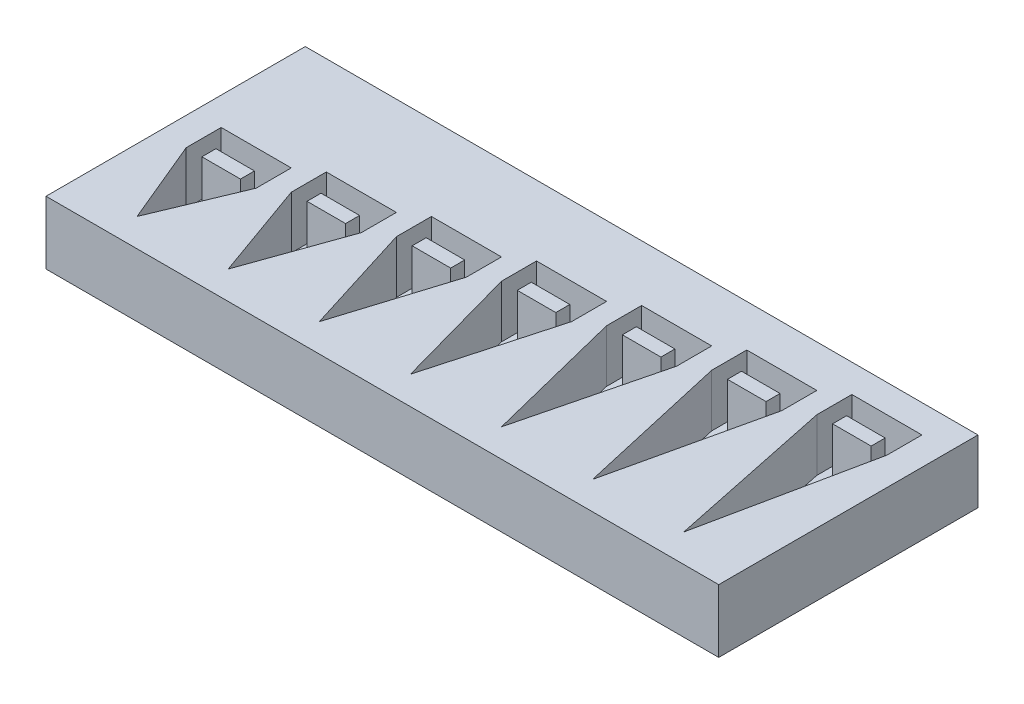
SolidWorks part; units mm, degrees
ref_plane "Front Plane" through (0, 0, 0) normal (0, 0, 1) x (1, 0, 0)
ref_plane "Top Plane" through (0, 0, 0) normal (0, 1, 0) x (1, 0, 0)
ref_plane "Right Plane" through (0, 0, 0) normal (1, 0, 0) x (0, 0, -1)
sketch "Flaps" plane through (0, 0, 0) normal (0, 1, 0) x (1, 0, 0)
  line L0 (0, 0) -> (0, 17) construction
  line L1 (0, 0) -> (-5, 12)
  line L2 (-5, 12) -> (-5, 17)
  line L3 (-5, 17) -> (5, 17)
  line L4 (5, 12) -> (5, 17)
  line L5 (0, 0) -> (5, 12)
  line L6 (13, 0) -> (13, 19) construction
  line L7 (-2.75, 14) -> (2.75, 14)
  line L8 (-2.75, 14) -> (-2.75, 12)
  line L9 (-2.75, 12) -> (2.75, 12)
  line L10 (2.75, 14) -> (2.75, 12)
  line L11 (13, 0) -> (8, 14)
  line L12 (8, 14) -> (8, 19)
  line L13 (8, 19) -> (18, 19)
  line L14 (18, 14) -> (18, 19)
  line L15 (13, 0) -> (18, 14)
  line L16 (10.25, 16) -> (15.75, 16)
  line L17 (10.25, 16) -> (10.25, 14)
  line L18 (10.25, 14) -> (15.75, 14)
  line L19 (15.75, 16) -> (15.75, 14)
  line L22 (26, 0) -> (26, 21) construction
  line L30 (26, 0) -> (21, 16)
  line L31 (21, 16) -> (21, 21)
  line L32 (21, 21) -> (31, 21)
  line L33 (31, 16) -> (31, 21)
  line L34 (26, 0) -> (31, 16)
  line L35 (23.25, 18) -> (28.75, 18)
  line L36 (23.25, 18) -> (23.25, 16)
  line L37 (23.25, 16) -> (28.75, 16)
  line L38 (28.75, 18) -> (28.75, 16)
  line L39 (39, 0) -> (39, 23) construction
  line L40 (39, 0) -> (34, 18)
  line L41 (34, 18) -> (34, 23)
  line L42 (34, 23) -> (44, 23)
  line L43 (44, 18) -> (44, 23)
  line L44 (39, 0) -> (44, 18)
  line L45 (36.25, 20) -> (41.75, 20)
  line L46 (36.25, 20) -> (36.25, 18)
  line L47 (36.25, 18) -> (41.75, 18)
  line L48 (41.75, 20) -> (41.75, 18)
  line L49 (52, 0) -> (52, 25) construction
  line L50 (52, 0) -> (47, 20)
  line L51 (47, 20) -> (47, 25)
  line L52 (47, 25) -> (57, 25)
  line L53 (57, 20) -> (57, 25)
  line L54 (52, 0) -> (57, 20)
  line L55 (49.25, 22) -> (54.75, 22)
  line L56 (49.25, 22) -> (49.25, 20)
  line L57 (49.25, 20) -> (54.75, 20)
  line L58 (54.75, 22) -> (54.75, 20)
  line L59 (65, 0) -> (65, 27) construction
  line L60 (65, 0) -> (60, 22)
  line L61 (60, 22) -> (60, 27)
  line L62 (60, 27) -> (70, 27)
  line L63 (70, 22) -> (70, 27)
  line L64 (65, 0) -> (70, 22)
  line L65 (62.25, 24) -> (67.75, 24)
  line L66 (62.25, 24) -> (62.25, 22)
  line L67 (62.25, 22) -> (67.75, 22)
  line L68 (67.75, 24) -> (67.75, 22)
  line L69 (78, 0) -> (78, 29) construction
  line L70 (78, 0) -> (73, 24)
  line L71 (73, 24) -> (73, 29)
  line L72 (73, 29) -> (83, 29)
  line L73 (83, 24) -> (83, 29)
  line L74 (78, 0) -> (83, 24)
  line L75 (75.25, 26) -> (80.75, 26)
  line L76 (75.25, 26) -> (75.25, 24)
  line L77 (75.25, 24) -> (80.75, 24)
  line L78 (80.75, 26) -> (80.75, 24)
  line L80 (-9, 33) -> (87, 33)
  line L81 (-9, 33) -> (-9, -4)
  line L82 (-9, -4) -> (87, -4)
  line L83 (87, 33) -> (87, -4)
  point P11 (0, 14)
  point P29 (13, 16)
  point P32 (26, 18)
  point P33 (87, 36.7759)
  point P34 (0, 0)
  point P45 (39, 20)
  point P57 (52, 22)
  point P58 (13, 0)
  point P69 (65, 24)
  point P70 (26, 0)
  point P81 (78, 26)
  point P82 (39, 0)
  point P83 (52, 0)
  point P84 (65, 0)
  point P85 (78, 0)
  dimension "D1" = 10
  dimension "D2" = 4
  dimension "L1" = 12
  dimension "D3" = 3
  dimension "PinDepth" = 2
  dimension "D5" = 5.5
  dimension "L2" = 14
  dimension "D8" = 7
  dimension "D9" = 13
  dimension "L3" = 16
  dimension "L4" = 18
  dimension "D11" = 4
  dimension "L5" = 20
  dimension "D13" = 4
  dimension "L6" = 22
  dimension "L7" = 24
  dimension "D17" = 4
extrude "Boss-Extrude1" add sketch "Flaps" along normal blind 7.5 contours L83 L80 L81 L82 L74 L70 L71 L72 L73 L64 L60 L61 L62 L63 L54 L50 L51 L52 L53 L44 L40 L41 L42 L43 L34 L30 L31 L32 L33 L15 L11 L12 L13 L14 L5 L1 L2 L3 L4 | L10 L7 L8 L9 | L19 L16 L17 L18 | L38 L35 L36 L37 | L48 L45 L46 L47 | L58 L55 L56 L57 | L68 L65 L66 L67 | L78 L75 L76 L77
sketch "Sketch2" plane through (0, 0, 0) normal (0, -1, 0) x (1, 0, 0)
  line L4 (87, -33) -> (87, 4)
  line L5 (87, 4) -> (-9, 4)
  line L6 (-9, 4) -> (-9, -33)
  line L7 (-9, -33) -> (87, -33)
  line L8 (87, -33) -> (87, 4)
  line L9 (87, 4) -> (-9, 4)
  line L10 (-9, 4) -> (-9, -33)
  line L11 (-9, -33) -> (87, -33)
  dimension "D1" = 0
extrude "Boss-Extrude2" add sketch "Sketch2" along normal blind 1.5
